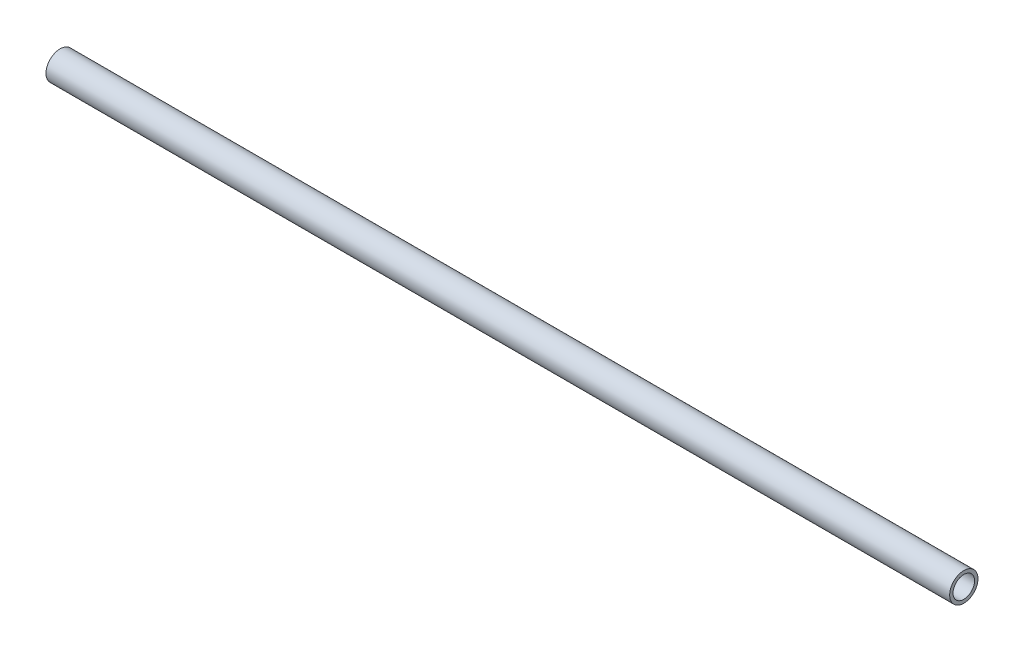
SolidWorks part; units mm, degrees
material "AISI 4130 Steel, annealed at 865C"
ref_plane "Front Plane" through (0, 0, 0) normal (0, 0, 1) x (1, 0, 0)
ref_plane "Top Plane" through (0, 0, 0) normal (0, 1, 0) x (1, 0, 0)
ref_plane "Right Plane" through (0, 0, 0) normal (1, 0, 0) x (0, 0, -1)
sketch "Sketch1" plane through (0, 0, 0) normal (1, 0, 0) x (0, 0, -1)
  circle A0 centre (0, 0) radius 12.7
  circle A1 centre (0, 0) radius 9.652
  dimension "D1" = 25.4
  dimension "D2" = 19.304
extrude "Boss-Extrude1" add sketch "Sketch1" along normal blind 810
